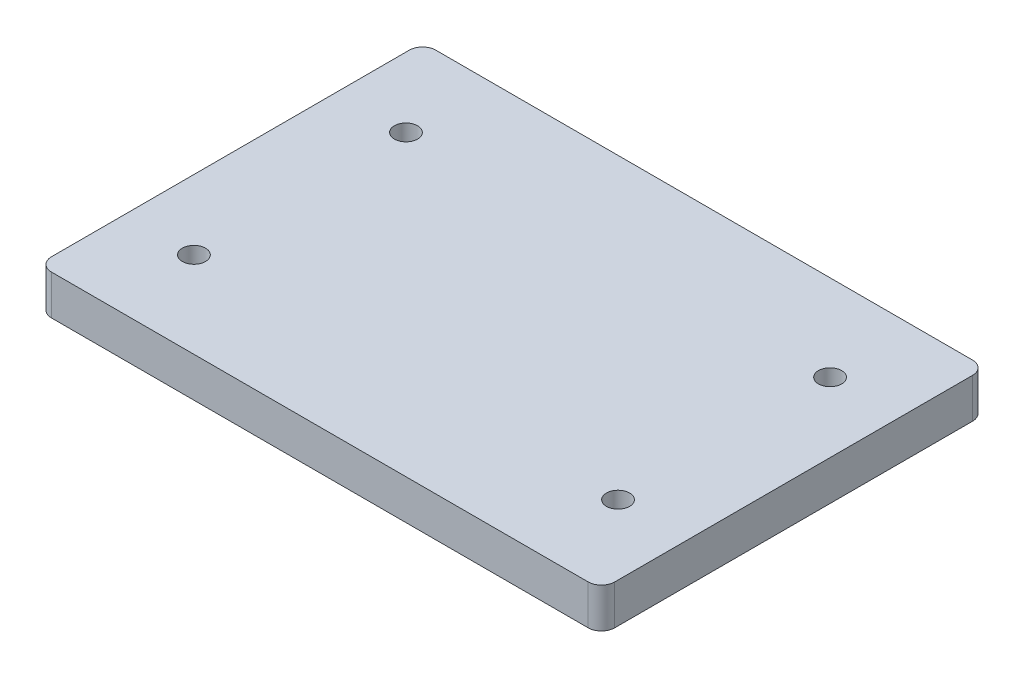
SolidWorks part; units mm, degrees
ref_plane "前视基准面" through (0, 0, 0) normal (0, 0, 1) x (1, 0, 0)
ref_plane "上视基准面" through (0, 0, 0) normal (0, 1, 0) x (1, 0, 0)
ref_plane "右视基准面" through (0, 0, 0) normal (1, 0, 0) x (0, 0, -1)
sketch "草图1" plane through (0, 0, 0) normal (0, 1, 0) x (1, 0, 0)
  line L1 (-42.5, -29) -> (42.5, -29)
  line L2 (-42.5, -29) -> (-42.5, 29)
  line L3 (-42.5, 29) -> (42.5, 29)
  line L4 (42.5, -29) -> (42.5, 29)
  line L5 (-42.5, -29) -> (42.5, 29) construction
  line L6 (-42.5, 29) -> (42.5, -29) construction
  point P0 (0, 0)
  dimension "D1" = 85
  dimension "D2" = 58
extrude "凸台-拉伸1" add sketch "草图1" along normal blind 6
fillet "圆角1" radius 2 4 edges at (-42.5, 3, -29) (42.5, 3, -29) (42.5, 3, 29) (-42.5, 3, 29)
sketch "草图2" plane through (0, 6, 0) normal (0, 1, 0) x (1, 0, 0)
  line L0 (-42.5, 0) -> (47.5074, 0) construction
  line L1 (-42.5, 27) -> (-42.5, -27) construction
  line L2 (0, 33.8366) -> (0, -34.5173) construction
  circle A0 centre (-32, 16) radius 1.75
  circle A1 centre (32, 16) radius 1.75
  circle A2 centre (32, -16) radius 1.75
  circle A3 centre (-32, -16) radius 1.75
  dimension "D1" = 3.5
  dimension "D2" = 64
  dimension "D3" = 32
extrude "切除-拉伸1" cut sketch "草图2" against normal blind 6
